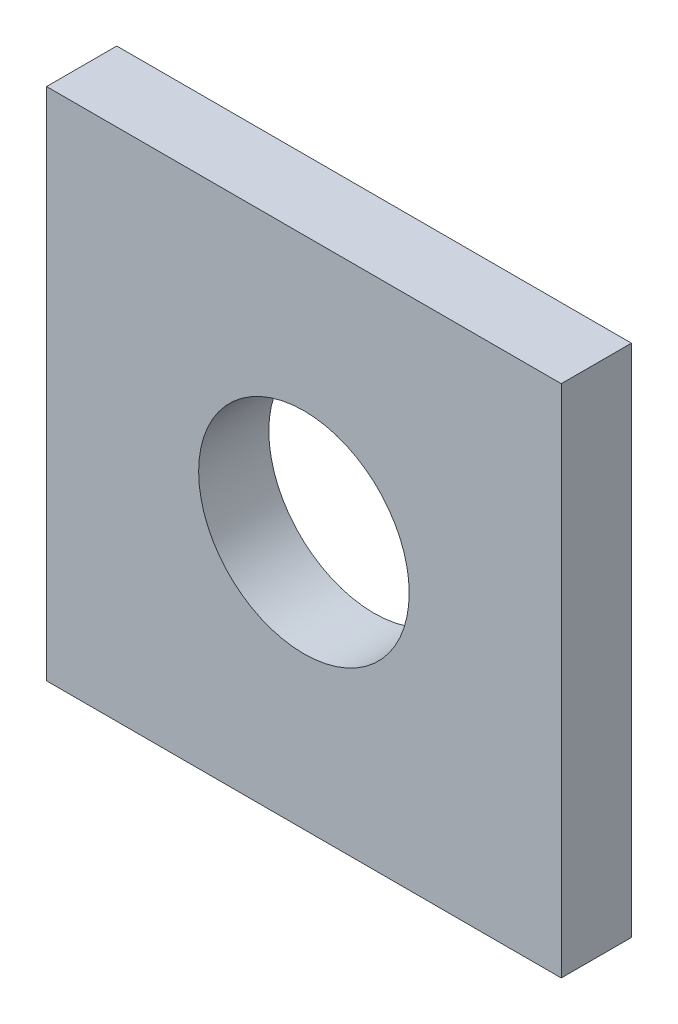
SolidWorks part; units mm, degrees
ref_plane "Front Plane" through (0, 0, 0) normal (0, 0, 1) x (1, 0, 0)
ref_plane "Top Plane" through (0, 0, 0) normal (0, 1, 0) x (1, 0, 0)
ref_plane "Right Plane" through (0, 0, 0) normal (1, 0, 0) x (0, 0, -1)
sketch "Sketch1" plane through (0, 0, 0) normal (0, 0, 1) x (1, 0, 0)
  line L1 (0, 0) -> (22, 0)
  line L2 (0, 0) -> (0, 22)
  line L3 (0, 22) -> (22, 22)
  line L4 (22, 0) -> (22, 22)
  circle A0 centre (11, 11) radius 4.5
  dimension "D3" = 9
  dimension "D1" = 22
  dimension "D2" = 22
  dimension "D4" = 11
  dimension "D5" = 11
extrude "Boss-Extrude1" add sketch "Sketch1" along normal blind 3
